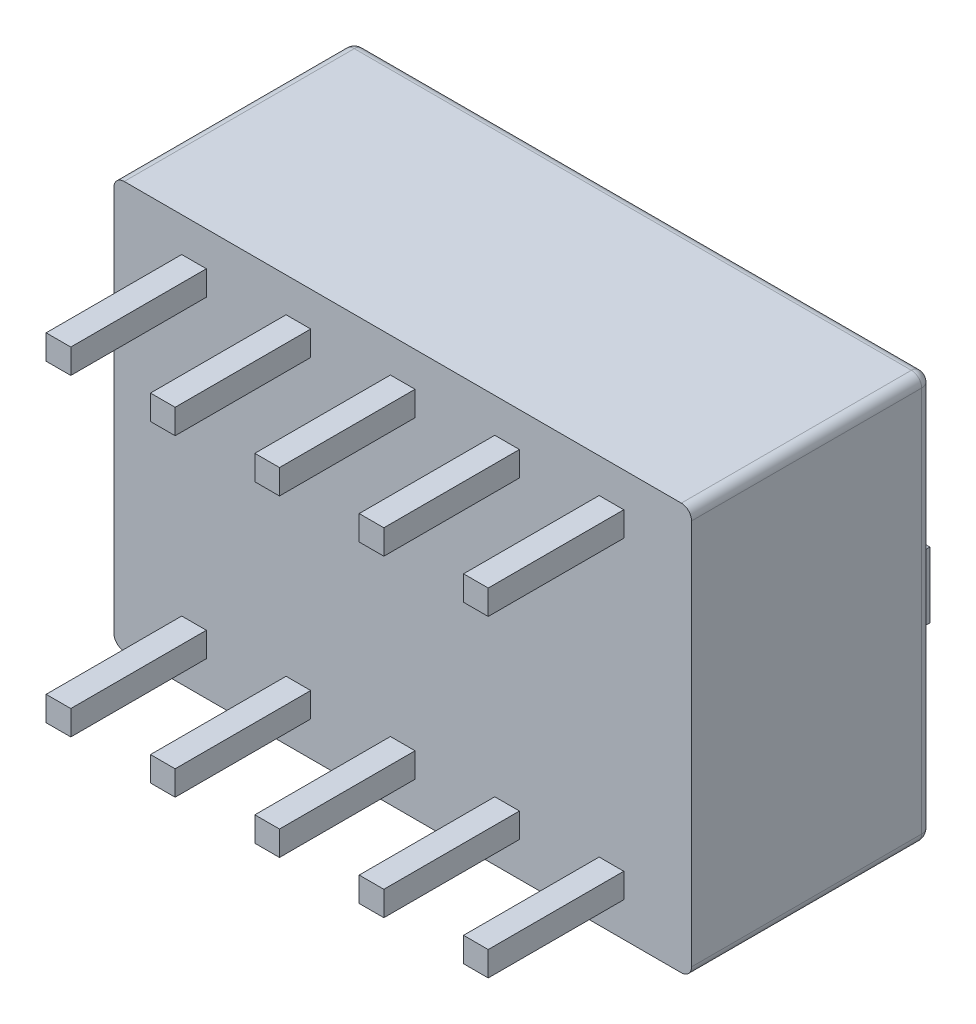
SolidWorks part; units mm, degrees
ref_plane "Ön Düzlem" through (0, 0, 0) normal (0, 0, 1) x (1, 0, 0)
ref_plane "Üst Düzlem" through (0, 0, 0) normal (0, 1, 0) x (1, 0, 0)
ref_plane "Sağ Düzlem" through (0, 0, 0) normal (1, 0, 0) x (0, 0, -1)
sketch "Çizim1" plane through (0, 0, 0) normal (0, 0, 1) x (1, 0, 0)
  line L1 (-7.03, 4.95) -> (7.03, 4.95)
  line L2 (-7.03, 4.95) -> (-7.03, -4.95)
  line L3 (-7.03, -4.95) -> (7.03, -4.95)
  line L4 (7.03, 4.95) -> (7.03, -4.95)
  line L5 (-7.03, 4.95) -> (7.03, -4.95) construction
  line L6 (-7.03, -4.95) -> (7.03, 4.95) construction
  point P0 (0, 0)
extrude "Yükseklik-Ekstrüzyon1" add sketch "Çizim1" along normal blind 5.85
sketch "Çizim2" plane through (0, 0, 0) normal (0, 0, -1) x (-1, 0, 0)
  line L7 (-5.78, -1.6) -> (-4.38, -1.6)
  line L8 (-5.78, -1.6) -> (-5.78, 1.6)
  line L9 (-5.78, 1.6) -> (-4.38, 1.6)
  line L10 (-4.38, -1.6) -> (-4.38, 1.6)
  line L11 (-5.78, -1.6) -> (-4.38, 1.6) construction
  line L12 (-5.78, 1.6) -> (-4.38, -1.6) construction
  line L13 (-3.24, -1.6) -> (-1.84, -1.6)
  line L14 (-3.24, -1.6) -> (-3.24, 1.6)
  line L15 (-3.24, 1.6) -> (-1.84, 1.6)
  line L16 (-1.84, -1.6) -> (-1.84, 1.6)
  line L17 (-3.24, -1.6) -> (-1.84, 1.6) construction
  line L18 (-3.24, 1.6) -> (-1.84, -1.6) construction
  line L19 (-0.7, -1.6) -> (0.7, -1.6)
  line L20 (-0.7, -1.6) -> (-0.7, 1.6)
  line L21 (-0.7, 1.6) -> (0.7, 1.6)
  line L22 (0.7, -1.6) -> (0.7, 1.6)
  line L23 (-0.7, -1.6) -> (0.7, 1.6) construction
  line L24 (-0.7, 1.6) -> (0.7, -1.6) construction
  line L25 (1.84, -1.6) -> (3.24, -1.6)
  line L26 (1.84, -1.6) -> (1.84, 1.6)
  line L27 (1.84, 1.6) -> (3.24, 1.6)
  line L28 (3.24, -1.6) -> (3.24, 1.6)
  line L29 (1.84, -1.6) -> (3.24, 1.6) construction
  line L30 (1.84, 1.6) -> (3.24, -1.6) construction
  line L31 (4.38, -1.6) -> (5.78, -1.6)
  line L32 (4.38, -1.6) -> (4.38, 1.6)
  line L33 (4.38, 1.6) -> (5.78, 1.6)
  line L34 (5.78, -1.6) -> (5.78, 1.6)
  line L35 (4.38, -1.6) -> (5.78, 1.6) construction
  line L36 (4.38, 1.6) -> (5.78, -1.6) construction
  point P0 (0, 0)
extrude "Kes-Ekstrüzyon1" cut sketch "Çizim2" against normal blind 1
sketch "Çizim3" plane through (0, 0, 1) normal (0, 0, -1) x (-1, 0, 0)
  line L0 (-4.38, -1.6) -> (-4.38, 1.6) construction
  line L1 (-5.78, -1.6) -> (-4.38, -1.6)
  line L2 (-5.78, -1.6) -> (-5.78, 0)
  line L3 (-5.78, 0) -> (-4.38, 0)
  line L4 (-4.38, -1.6) -> (-4.38, 0)
  line L5 (-1.84, -1.6) -> (-1.84, 1.6) construction
  line L6 (-3.24, -1.6) -> (-1.84, -1.6)
  line L7 (-3.24, -1.6) -> (-3.24, 0)
  line L8 (-3.24, 0) -> (-1.84, 0)
  line L9 (-1.84, -1.6) -> (-1.84, 0)
  line L10 (0.7, -1.6) -> (0.7, 1.6) construction
  line L11 (-0.7, -1.6) -> (0.7, -1.6)
  line L12 (-0.7, -1.6) -> (-0.7, 0)
  line L13 (-0.7, 0) -> (0.7, 0)
  line L14 (0.7, -1.6) -> (0.7, 0)
  line L15 (3.24, -1.6) -> (3.24, 1.6) construction
  line L16 (1.84, -1.6) -> (3.24, -1.6)
  line L17 (1.84, -1.6) -> (1.84, 0)
  line L18 (1.84, 0) -> (3.24, 0)
  line L19 (3.24, -1.6) -> (3.24, 0)
  line L20 (5.78, -1.6) -> (5.78, 1.6) construction
  line L21 (4.38, -1.6) -> (5.78, -1.6)
  line L22 (4.38, -1.6) -> (4.38, 0)
  line L23 (4.38, 0) -> (5.78, 0)
  line L24 (5.78, -1.6) -> (5.78, 0)
extrude "Yükseklik-Ekstrüzyon2" add sketch "Çizim3" along normal blind 2.2 separate body
sketch "Çizim4" plane through (0, 0, 1) normal (0, 0, -1) x (-1, 0, 0)
  line L0 (-5.78, 1.6) -> (-5.78, -1.6) construction
  line L1 (-5.78, 0) -> (-4.38, 0)
  line L2 (-5.78, 0) -> (-5.78, 1.6)
  line L3 (-5.78, 1.6) -> (-4.38, 1.6)
  line L4 (-4.38, 0) -> (-4.38, 1.6)
  line L5 (-3.24, 1.6) -> (-3.24, -1.6) construction
  line L6 (-3.24, 0) -> (-1.84, 0)
  line L7 (-3.24, 0) -> (-3.24, 1.6)
  line L8 (-3.24, 1.6) -> (-1.84, 1.6)
  line L9 (-1.84, 0) -> (-1.84, 1.6)
  line L10 (-0.7, 1.6) -> (-0.7, -1.6) construction
  line L11 (-0.7, 0) -> (0.7, 0)
  line L12 (-0.7, 0) -> (-0.7, 1.6)
  line L13 (-0.7, 1.6) -> (0.7, 1.6)
  line L14 (0.7, 0) -> (0.7, 1.6)
  line L15 (1.84, 1.6) -> (1.84, -1.6) construction
  line L16 (1.84, 0) -> (3.24, 0)
  line L17 (1.84, 0) -> (1.84, 1.6)
  line L18 (1.84, 1.6) -> (3.24, 1.6)
  line L19 (3.24, 0) -> (3.24, 1.6)
  line L21 (4.38, 0) -> (5.78, 0)
  line L22 (4.38, 0) -> (4.38, 1.6)
  line L23 (4.38, 1.6) -> (5.78, 1.6)
  line L24 (5.78, 0) -> (5.78, 1.6)
extrude "Yükseklik-Ekstrüzyon3" add sketch "Çizim4" along normal blind 0.9 separate body
fillet "Radyus1" radius 0.25 8 edges at (7.03, -4.95, 2.925) (7.03, 4.95, 2.925) (7.03, 0, 0) (0, -4.95, 0) (-7.03, -4.95, 2.925) (-7.03, 4.95, 2.925) (0, 4.95, 0) (-7.03, 0, 0)
sketch "Çizim5" plane through (0, 0, 5.85) normal (0, 0, 1) x (1, 0, 0)
  line L12 (-5.38, -4.11) -> (-4.78, -4.11)
  line L13 (-5.38, -4.11) -> (-5.38, -3.51)
  line L14 (-5.38, -3.51) -> (-4.78, -3.51)
  line L15 (-4.78, -4.11) -> (-4.78, -3.51)
  line L16 (-5.38, -4.11) -> (-4.78, -3.51) construction
  line L17 (-5.38, -3.51) -> (-4.78, -4.11) construction
  line L18 (-5.38, 3.51) -> (-4.78, 3.51)
  line L19 (-5.38, 3.51) -> (-5.38, 4.11)
  line L20 (-5.38, 4.11) -> (-4.78, 4.11)
  line L21 (-4.78, 3.51) -> (-4.78, 4.11)
  line L22 (-5.38, 3.51) -> (-4.78, 4.11) construction
  line L23 (-5.38, 4.11) -> (-4.78, 3.51) construction
  line L24 (-2.84, -4.11) -> (-2.24, -4.11)
  line L25 (-2.84, -4.11) -> (-2.84, -3.51)
  line L26 (-2.84, -3.51) -> (-2.24, -3.51)
  line L27 (-2.24, -4.11) -> (-2.24, -3.51)
  line L28 (-2.84, -4.11) -> (-2.24, -3.51) construction
  line L29 (-2.84, -3.51) -> (-2.24, -4.11) construction
  line L30 (-2.84, 3.51) -> (-2.24, 3.51)
  line L31 (-2.84, 3.51) -> (-2.84, 4.11)
  line L32 (-2.84, 4.11) -> (-2.24, 4.11)
  line L33 (-2.24, 3.51) -> (-2.24, 4.11)
  line L34 (-2.84, 3.51) -> (-2.24, 4.11) construction
  line L35 (-2.84, 4.11) -> (-2.24, 3.51) construction
  line L36 (-0.3, 3.51) -> (0.3, 3.51)
  line L37 (-0.3, 3.51) -> (-0.3, 4.11)
  line L38 (-0.3, 4.11) -> (0.3, 4.11)
  line L39 (0.3, 3.51) -> (0.3, 4.11)
  line L40 (-0.3, 3.51) -> (0.3, 4.11) construction
  line L41 (-0.3, 4.11) -> (0.3, 3.51) construction
  line L42 (-0.3, -4.11) -> (0.3, -4.11)
  line L43 (-0.3, -4.11) -> (-0.3, -3.51)
  line L44 (-0.3, -3.51) -> (0.3, -3.51)
  line L45 (0.3, -4.11) -> (0.3, -3.51)
  line L46 (-0.3, -4.11) -> (0.3, -3.51) construction
  line L47 (-0.3, -3.51) -> (0.3, -4.11) construction
  line L48 (2.24, -4.11) -> (2.84, -4.11)
  line L49 (2.24, -4.11) -> (2.24, -3.51)
  line L50 (2.24, -3.51) -> (2.84, -3.51)
  line L51 (2.84, -4.11) -> (2.84, -3.51)
  line L52 (2.24, -4.11) -> (2.84, -3.51) construction
  line L53 (2.24, -3.51) -> (2.84, -4.11) construction
  line L54 (2.24, 3.51) -> (2.84, 3.51)
  line L55 (2.24, 3.51) -> (2.24, 4.11)
  line L56 (2.24, 4.11) -> (2.84, 4.11)
  line L57 (2.84, 3.51) -> (2.84, 4.11)
  line L58 (2.24, 3.51) -> (2.84, 4.11) construction
  line L59 (2.24, 4.11) -> (2.84, 3.51) construction
  line L60 (4.78, -4.11) -> (5.38, -4.11)
  line L61 (4.78, -4.11) -> (4.78, -3.51)
  line L62 (4.78, -3.51) -> (5.38, -3.51)
  line L63 (5.38, -4.11) -> (5.38, -3.51)
  line L64 (4.78, -4.11) -> (5.38, -3.51) construction
  line L65 (4.78, -3.51) -> (5.38, -4.11) construction
  line L66 (4.78, 3.51) -> (5.38, 3.51)
  line L67 (4.78, 3.51) -> (4.78, 4.11)
  line L68 (4.78, 4.11) -> (5.38, 4.11)
  line L69 (5.38, 3.51) -> (5.38, 4.11)
  line L70 (4.78, 3.51) -> (5.38, 4.11) construction
  line L71 (4.78, 4.11) -> (5.38, 3.51) construction
  point P0 (0, 0)
extrude "Yükseklik-Ekstrüzyon4" add sketch "Çizim5" along normal blind 3.3
